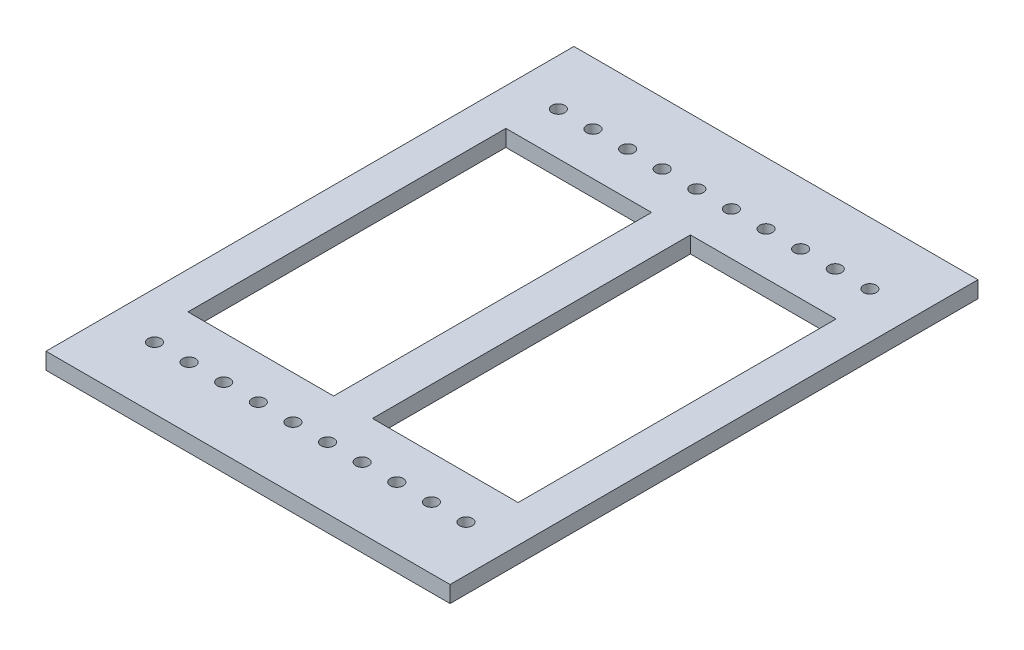
SolidWorks part; units mm, degrees
material "PTFE (general)"
ref_plane "Front Plane" through (0, 0, 0) normal (0, 0, 1) x (1, 0, 0)
ref_plane "Top Plane" through (0, 0, 0) normal (0, 1, 0) x (1, 0, 0)
ref_plane "Right Plane" through (0, 0, 0) normal (1, 0, 0) x (0, 0, -1)
sketch "Sketch1" plane through (0, 0, 0) normal (0, 1, 0) x (1, 0, 0)
  line L0 (10.39, 27.15) -> (10.39, 0) construction
  line L1 (0, 0) -> (20.78, 0)
  line L2 (0, 0) -> (0, 27.15)
  line L3 (0, 27.15) -> (20.78, 27.15)
  line L4 (20.78, 0) -> (20.78, 27.15)
  line L5 (18.88, 5.4) -> (11.39, 5.4)
  line L6 (1.9, 21.75) -> (9.39, 21.75)
  line L7 (1.9, 21.75) -> (1.9, 5.4)
  line L8 (1.9, 5.4) -> (9.39, 5.4)
  line L9 (9.39, 21.75) -> (9.39, 5.4)
  line L10 (11.39, 21.75) -> (11.39, 5.4)
  line L11 (18.88, 21.75) -> (18.88, 5.4)
  line L12 (18.88, 21.75) -> (11.39, 21.75)
  line L13 (0, 23.96) -> (20.78, 23.96) construction
  line L14 (0, 13.575) -> (20.78, 13.575) construction
  circle A0 centre (2.389, 23.96) radius 0.33
  circle A1 centre (4.169, 23.96) radius 0.33
  circle A2 centre (5.949, 23.96) radius 0.33
  circle A3 centre (7.729, 23.96) radius 0.33
  circle A4 centre (9.509, 23.96) radius 0.33
  circle A5 centre (11.289, 23.96) radius 0.33
  circle A6 centre (13.069, 23.96) radius 0.33
  circle A7 centre (14.849, 23.96) radius 0.33
  circle A8 centre (16.629, 23.96) radius 0.33
  circle A9 centre (18.409, 23.96) radius 0.33
  circle A10 centre (18.409, 3.19) radius 0.33
  circle A11 centre (16.629, 3.19) radius 0.33
  circle A12 centre (14.849, 3.19) radius 0.33
  circle A13 centre (13.069, 3.19) radius 0.33
  circle A14 centre (11.289, 3.19) radius 0.33
  circle A15 centre (9.509, 3.19) radius 0.33
  circle A16 centre (7.729, 3.19) radius 0.33
  circle A17 centre (5.949, 3.19) radius 0.33
  circle A18 centre (4.169, 3.19) radius 0.33
  circle A19 centre (2.389, 3.19) radius 0.33
  point P19 (2.389, 23.96)
  dimension "D9" = 0.66
  dimension "D1" = 27.15
  dimension "D2" = 20.78
  dimension "D3" = 5.4
  dimension "D4" = 5.4
  dimension "D5" = 1
  dimension "D6" = 1.9
  dimension "D7" = 3.19
  dimension "D8" = 2.389
  dimension "D10" = 10
extrude "Boss-Extrude1" add sketch "Sketch1" along normal blind 0.85
